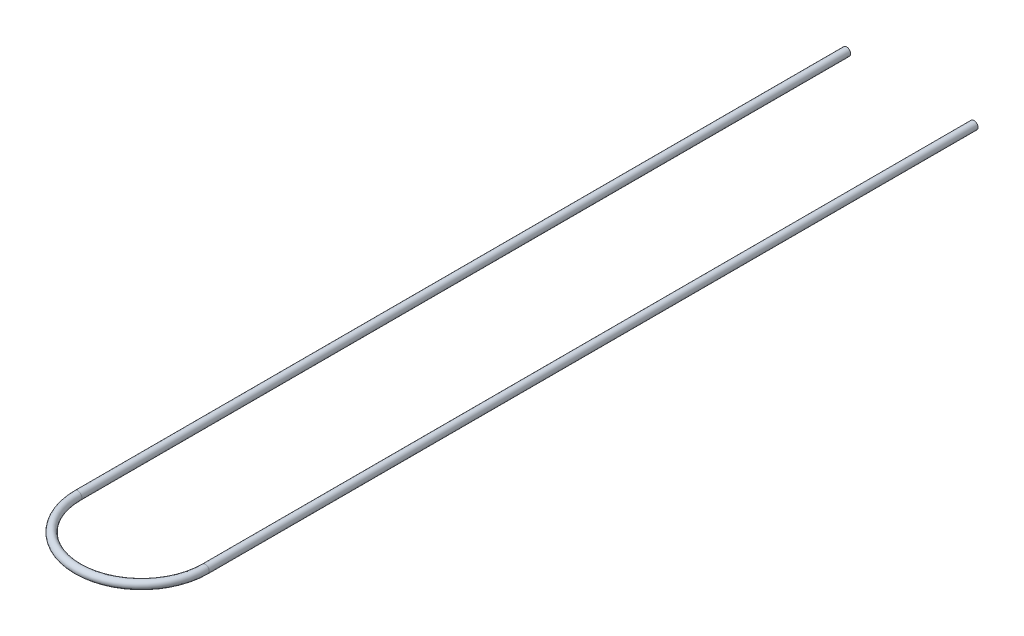
SolidWorks part; units mm, degrees
ref_plane "Front Plane" through (0, 0, 0) normal (0, 0, 1) x (1, 0, 0)
ref_plane "Top Plane" through (0, 0, 0) normal (0, 1, 0) x (1, 0, 0)
ref_plane "Right Plane" through (0, 0, 0) normal (1, 0, 0) x (0, 0, -1)
sketch "Sketch1" plane through (0, 0, 0) normal (0, 1, 0) x (1, 0, 0)
  line L0 (314.7, -300) -> (314.7, -2440)
  line L2 (-40, -300) -> (-40, -2440)
  arc A0 (-40, -2440) -> (314.7, -2440) centre (137.35, -2440) ccw
  dimension "D1" = 2140
  dimension "D2" = 354.7
ref_plane "Plane1" through (314.7, 0, 300) normal (0, 0, -1) x (-1, 0, 0)
sketch "Sketch2" plane through (314.7, 0, 300) normal (0, 0, -1) x (-1, 0, 0)
  circle A0 centre (0, 0) radius 9.95
  circle A1 centre (0, 0) radius 11.1
  dimension "D1" = 22.2
  dimension "D2" = 19.9
sweep "Sweep1" add profiles "Sketch2" path "Sketch1"
